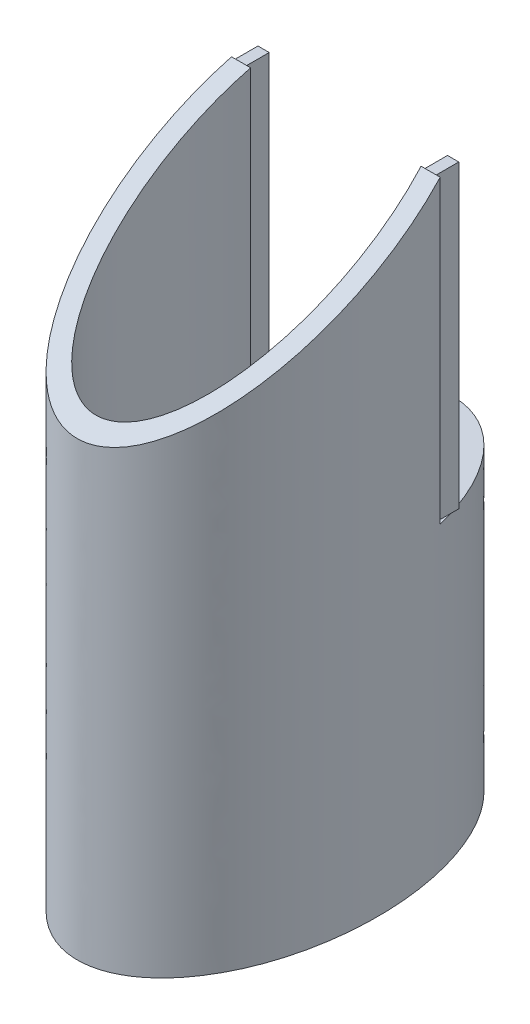
SolidWorks part; units mm, degrees
ref_plane "Front Plane" through (0, 0, 0) normal (0, 0, 1) x (1, 0, 0)
ref_plane "Top Plane" through (0, 0, 0) normal (0, 1, 0) x (1, 0, 0)
ref_plane "Right Plane" through (0, 0, 0) normal (1, 0, 0) x (0, 0, -1)
sketch "Sketch1" plane through (0, 0, 0) normal (0, 1, 0) x (1, 0, 0)
  line L0 (0, 0) -> (0, 31.1744) construction
  ellipse E0 centre (0, 0) end of major axis (0, 25) minor radius 15
  ellipse E1 centre (0, 0) end of major axis (0, 22.5) minor radius 12.5
  dimension "D1" = 15
  dimension "D2" = 25
  dimension "D3" = 22.5
  dimension "D4" = 12.5
sketch "Sketch2" plane through (0, 0, 0) normal (1, 0, 0) x (0, 0, -1)
  line L0 (0, 0) -> (5.1273, 29.0784) construction
  line L1 (22.5, 0) -> (-22.5, 0) construction
  dimension "D1" = 80
extrude "Boss-Extrude1" add sketch "Sketch1" along normal blind 80
sketch "Sketch5" plane through (0, 0, 0) normal (1, 0, 0) x (0, 0, -1)
  line L0 (9.4324, 80) -> (-25, 60.1255)
  line L1 (25, 80) -> (-25, 80) construction
  line L2 (-25, 80) -> (-25, 0) construction
  line L3 (-25, 60.1255) -> (-25, 80)
  line L4 (-25, 80) -> (9.4324, 80)
extrude "Cut-Extrude1" cut sketch "Sketch5" against normal through all both and the other way through all
sketch "Sketch6" plane through (0, 0, 0) normal (1, 0, 0) x (0, 0, -1)
  line L0 (25, 0) -> (25, 80) construction
  line L1 (25, 80) -> (9.4324, 80)
  line L2 (25, 80) -> (25, 40)
  line L3 (25, 40) -> (9.4324, 40)
  line L4 (9.4324, 80) -> (9.4324, 40)
  line L5 (25, 80) -> (9.4324, 80) construction
  point P6 (0, 0)
  point P9 (9.4324, 78.7846)
  dimension "D1" = 40
extrude "Cut-Extrude2" cut sketch "Sketch6" against normal through all both and the other way through all
sketch "Sketch10" plane through (0, 0, -9.4324) normal (0, 0, -1) x (-1, 0, 0)
  line L0 (-12.62, 80) -> (-12.62, 40) construction
  line L1 (-11.3486, 80) -> (-13.8914, 80) construction
  line L2 (-11.3486, 40) -> (-13.8914, 40) construction
  line L4 (-13.37, 80) -> (-11.87, 80)
  line L5 (-13.37, 80) -> (-13.37, 40)
  line L6 (-13.37, 40) -> (-11.87, 40)
  line L7 (-11.87, 80) -> (-11.87, 40)
  dimension "D1" = 1.5
extrude "Boss-Extrude2" add sketch "Sketch10" along normal blind 3
mirror "Mirror1" about plane through (0, 0, 0) normal (1, 0, 0) of "Boss-Extrude2"
